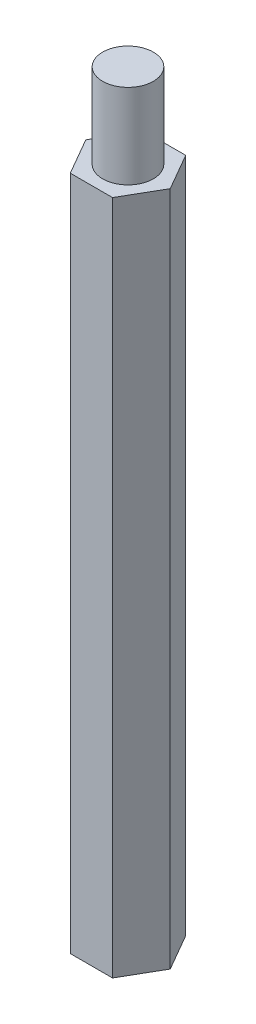
SolidWorks part; units mm, degrees
material "2.0402 (CuZn40Pb2)"
ref_plane "Front" through (0, 0, 0) normal (0, 0, 1) x (1, 0, 0)
ref_plane "Top" through (0, 0, 0) normal (0, 1, 0) x (1, 0, 0)
ref_plane "Right" through (0, 0, 0) normal (1, 0, 0) x (0, 0, -1)
sketch "Эскиз1" plane through (0, 0, 0) normal (0, 1, 0) x (1, 0, 0)
  line L1 (1.25, -2.1651) -> (2.5, 0)
  line L2 (2.5, 0) -> (1.25, 2.1651)
  line L3 (1.25, 2.1651) -> (-1.25, 2.1651)
  line L4 (-1.25, 2.1651) -> (-2.5, 0)
  line L5 (-2.5, 0) -> (-1.25, -2.1651)
  line L6 (-1.25, -2.1651) -> (1.25, -2.1651)
  circle A0 centre (0, 0) radius 2.1651 construction
  circle A1 centre (0, 0) radius 2.5 construction
  dimension "D1" = 5
  dimension "D2" = 2.5
extrude "Бобышка-Вытянуть1" add sketch "Эскиз1" along normal blind 40
sketch "Эскиз2" plane through (0, 40, 0) normal (0, 1, 0) x (1, 0, 0)
  circle A0 centre (0, 0) radius 1.5
  dimension "D1" = 3
extrude "Бобышка-Вытянуть2" add sketch "Эскиз2" along normal blind 5
sketch "Эскиз3" plane through (0, 0, 0) normal (0, -1, 0) x (1, 0, 0)
  circle A0 centre (0, 0) radius 1.5
  dimension "D1" = 3
extrude "Вырез-Вытянуть1" cut sketch "Эскиз3" against normal blind 10
